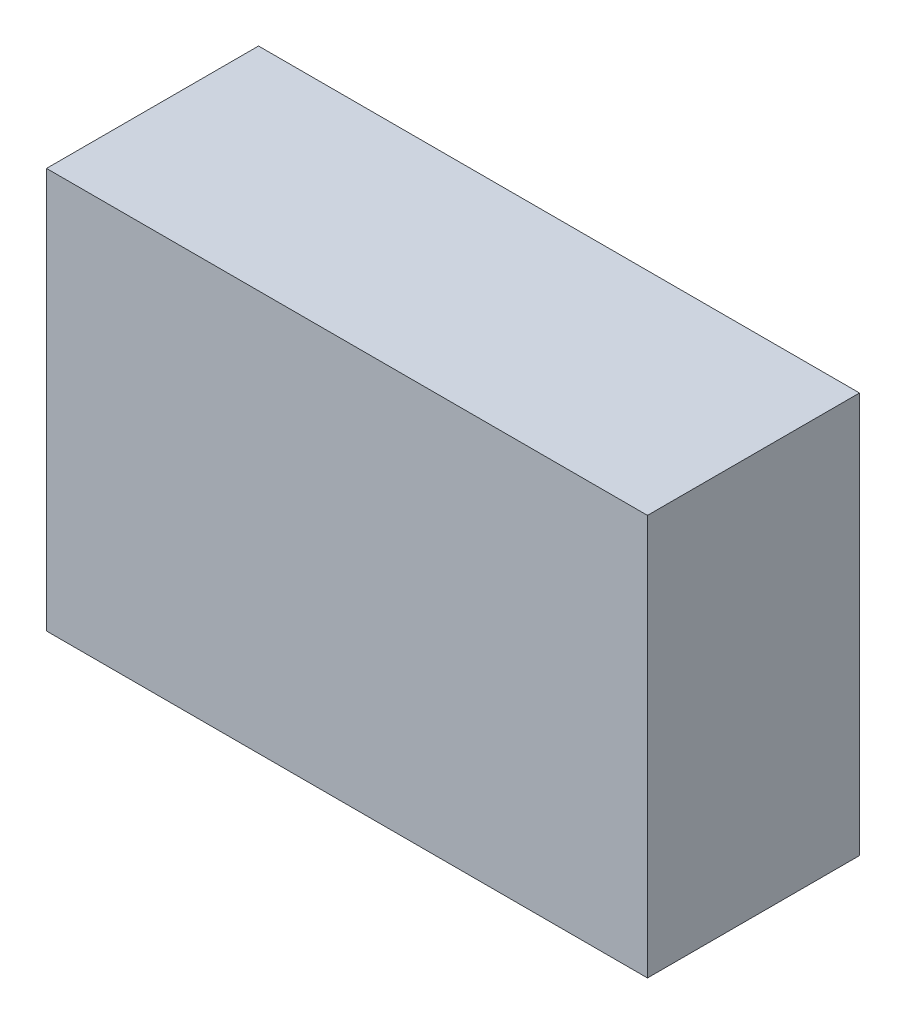
SolidWorks part; units mm, degrees
material "Ductile Iron"
ref_plane "Front Plane" through (0, 0, 0) normal (0, 0, 1) x (1, 0, 0)
ref_plane "Top Plane" through (0, 0, 0) normal (0, 1, 0) x (1, 0, 0)
ref_plane "Right Plane" through (0, 0, 0) normal (1, 0, 0) x (0, 0, -1)
sketch "Sketch1" plane through (0, 0, 0) normal (0, 0, 1) x (1, 0, 0)
  line L6 (9, 88.5) -> (-9, 88.5)
  line L7 (9, 76.5) -> (9, 88.5)
  line L8 (-9, 76.5) -> (9, 76.5)
  line L9 (-9, 88.5) -> (-9, 76.5)
  line L10 (9, 88.5) -> (-9, 88.5)
  line L11 (9, 76.5) -> (9, 88.5)
  line L12 (-9, 76.5) -> (9, 76.5)
  line L13 (-9, 88.5) -> (-9, 76.5)
  dimension "D1" = 0
extrude "Boss-Extrude1" add sketch "Sketch1" against normal up to surface (6.35 mm away)
